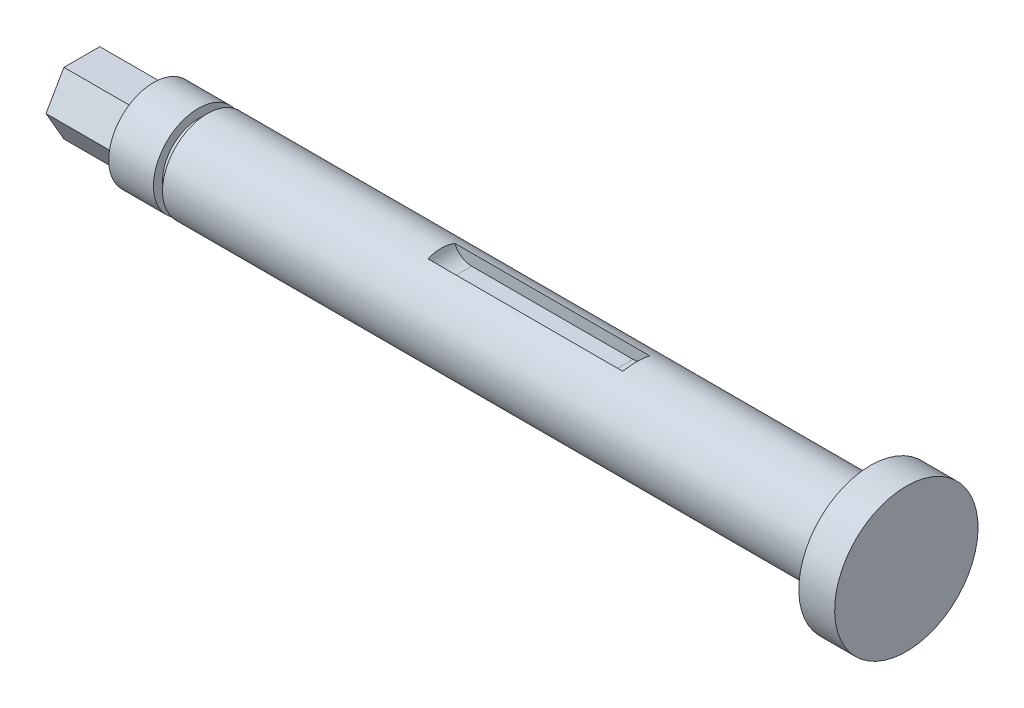
SolidWorks part; units mm, degrees
ref_plane "Front Plane" through (0, 0, 0) normal (0, 0, 1) x (1, 0, 0)
ref_plane "Top Plane" through (0, 0, 0) normal (0, 1, 0) x (1, 0, 0)
ref_plane "Right Plane" through (0, 0, 0) normal (1, 0, 0) x (0, 0, -1)
sketch "Sketch1" plane through (0, 0, 0) normal (0, 0, 1) x (1, 0, 0)
  line L0 (-46.1818, -7.8512) -> (-46.1818, -1.5012)
  line L1 (-46.1818, -1.5012) -> (-33.4818, -1.5012)
  line L2 (-33.4818, -1.5012) -> (-33.4818, 0.0863)
  line L3 (-33.4818, 0.0863) -> (-25.557, 0.0863)
  line L7 (-23.9568, 0.0863) -> (93.5182, 0.0863)
  line L11 (99.8682, -7.8512) -> (-46.1818, -7.8512)
  line L12 (-46.1818, -7.8512) -> (-88.9, -7.8512) construction
  line L13 (99.8682, -7.8512) -> (127.6254, -7.8512) construction
  line L14 (99.8682, -7.8512) -> (99.8682, 4.8488)
  line L15 (99.8682, 4.8488) -> (93.5182, 4.8488)
  line L16 (93.5182, 4.8488) -> (93.5182, 0.0863)
  line L17 (-23.9568, 0.0863) -> (-23.9568, -1.5139)
  line L18 (-25.557, 0.0863) -> (-25.557, -1.5139)
  line L19 (-25.557, -1.5139) -> (-23.9568, -1.5139)
  point P14 (-29.5194, 0.0863)
  dimension "D1" = 6.35
  dimension "D2" = 25.4
  dimension "D3" = 15.875
  dimension "D4" = 12.7
  dimension "D5" = 15.875
  dimension "D6" = 133.35
  dimension "D7" = 12.7
  dimension "D8" = 117.475
  dimension "D9" = 1.6002
  dimension "D10" = 1.6002
revolve "Revolve1" add sketch "Sketch1" angle 360 about L12
sketch "Sketch2" plane through (0, 0, 0) normal (0, 0, 1) x (1, 0, 0)
  line L0 (17.3182, 5.7814) -> (17.3182, 0.8737)
  line L2 (20.4932, -2.3013) -> (49.0682, -2.3013)
  line L3 (52.2432, 0.8737) -> (52.2432, 5.7814)
  line L4 (52.2432, 5.7814) -> (17.3182, 5.7814)
  line L5 (93.5182, 0.0863) -> (-23.9568, 0.0863) construction
  arc A2 (17.3182, 0.8737) -> (20.4932, -2.3013) centre (20.4932, 0.8737) ccw
  arc A3 (49.0682, -2.3013) -> (52.2432, 0.8737) centre (49.0682, 0.8737) ccw
  dimension "D1" = 2.3876
  dimension "D2" = 3.175
  dimension "D3" = 3.175
  dimension "D4" = 34.925
  dimension "D5" = 4.9077
  dimension "D6" = 63.5
extrude "Cut-Extrude1" cut sketch "Sketch2" against normal mid plane 4.7625
sketch "Sketch3" plane through (-46.1818, 0, 0) normal (-1, 0, 0) x (0, 0, 1)
  line L7 (6.35, -7.8512) -> (3.175, -2.3519)
  line L8 (3.175, -2.3519) -> (-3.175, -2.3519)
  line L9 (-3.175, -2.3519) -> (-6.35, -7.8512)
  line L10 (-6.35, -7.8512) -> (-3.175, -13.3505)
  line L11 (-3.175, -13.3505) -> (3.175, -13.3505)
  line L12 (3.175, -13.3505) -> (6.35, -7.8512)
  circle A0 centre (0, -7.8512) radius 6.35 construction
extrude "Cut-Extrude2" cut sketch "Sketch3" against normal up to surface (12.7 mm away) flip side to cut up to face at (-33.4818, -1.5012, 0)
